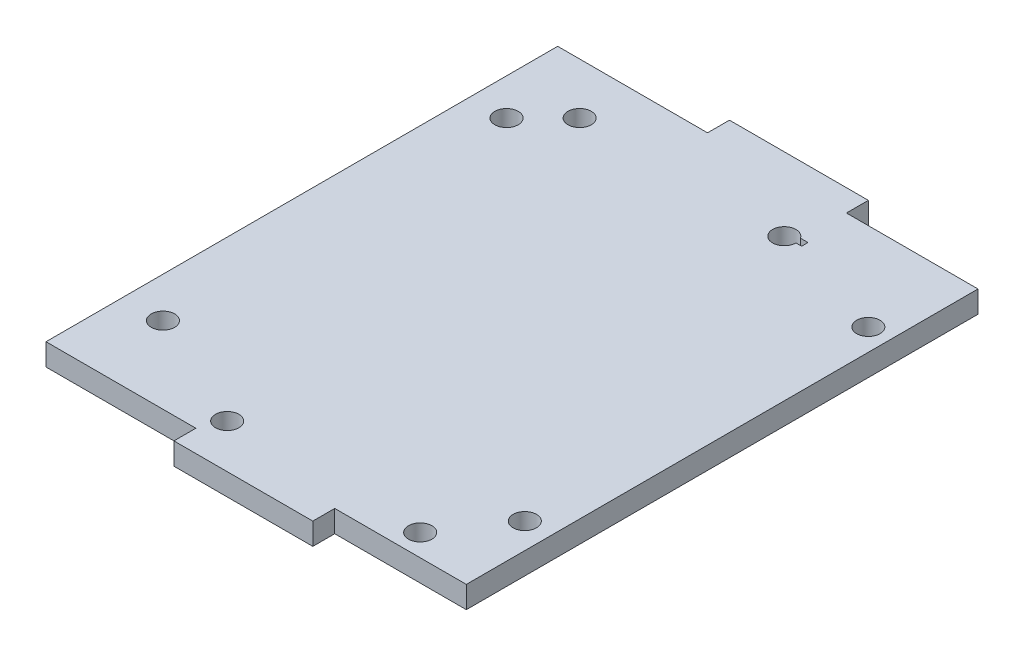
SolidWorks part; units mm, degrees
ref_plane "Front Plane" through (0, 0, 0) normal (0, 0, 1) x (1, 0, 0)
ref_plane "Top Plane" through (0, 0, 0) normal (0, 1, 0) x (1, 0, 0)
ref_plane "Right Plane" through (0, 0, 0) normal (1, 0, 0) x (0, 0, -1)
sketch "Sketch1" plane through (0, 0, 0) normal (0, 1, 0) x (1, 0, 0)
  line L0 (63.7979, -35) -> (63.7979, 35)
  line L1 (8.7979, 35) -> (6.2979, 35)
  line L2 (6.2979, 35) -> (6.2979, -35)
  line L3 (6.2979, -35) -> (8.7979, -35)
  line L5 (45.8979, 28) -> (46.6681, 28)
  line L7 (8.7979, 35) -> (26.7979, 35)
  line L8 (26.7979, 35) -> (26.7979, 38)
  line L9 (26.7979, 38) -> (45.7979, 38)
  line L10 (45.7979, 38) -> (45.7979, 35)
  line L11 (45.7979, 35) -> (63.7979, 35)
  line L12 (45.6375, 28.8749) -> (46.6681, 28.8749)
  line L13 (0, 0) -> (58, 0) construction
  line L14 (46.6681, 28) -> (46.6681, 28.8749)
  line L18 (61, -35) -> (63.7979, -35)
  line L19 (61, 35) -> (63.7979, 35)
  line L25 (36.2979, -34.5) -> (36.2979, 34.5) construction
  line L31 (9.2979, 34.5) -> (63.2979, -34.5) construction
  line L32 (9.2979, -34.5) -> (63.2979, 34.5) construction
  line L37 (61, -35) -> (63.7979, -35)
  line L38 (45.7979, -35) -> (63.7979, -35)
  line L39 (45.7979, -38) -> (45.7979, -35)
  line L40 (26.7979, -38) -> (45.7979, -38)
  line L41 (26.7979, -35) -> (26.7979, -38)
  line L42 (8.7979, -35) -> (26.7979, -35)
  circle A0 centre (11.7979, -24.5) radius 1.6
  circle A1 centre (60.2979, -23.5) radius 1.6
  circle A2 centre (16.2979, 28) radius 1.6
  arc A3 (45.6375, 28.8749) -> (45.8979, 28) centre (44.2979, 28) ccw
  point P29 (36.2979, 0)
  dimension "D14" = 3.2
  dimension "D17" = 3.2
  dimension "D18" = 3.2
  dimension "D19" = 3.2
  dimension "D8" = 28
  dimension "D3" = 48.5
  dimension "D4" = 19
  dimension "D5" = 18
  dimension "D6" = 26.7979
  dimension "D7" = 18
  dimension "D9" = 52.5
  dimension "D10" = 51.5
  dimension "D11" = 3
  dimension "D12" = 69
  dimension "D13" = 7
  dimension "D15" = 2.5
  dimension "D16" = 4.5
  dimension "D23" = 19
extrude "Boss-Extrude1" add sketch "Sketch1" along normal blind 3
sketch "Sketch3" plane through (0, 0, 0) normal (0, -1, 0) x (1, 0, 0)
  line L0 (6.2979, -35) -> (6.2979, 35) construction
  line L1 (6.2979, -35) -> (26.7979, -35) construction
  line L2 (45.7979, -35) -> (63.7979, -35) construction
  circle A0 centre (11.2979, -23) radius 1.6
  circle A1 centre (60.7979, -23) radius 1.6
  circle A2 centre (54.4879, 32) radius 1.6
  circle A3 centre (28.0879, 32) radius 1.6
  dimension "D1" = 3.2
  dimension "D2" = 3.2
  dimension "D3" = 3.2
  dimension "D4" = 3.2
  dimension "D5" = 5
  dimension "D6" = 12
  dimension "D7" = 12
  dimension "D8" = 49.5
  dimension "D9" = 6.31
  dimension "D10" = 55
  dimension "D11" = 26.4
extrude "Cut-Extrude1" cut sketch "Sketch3" against normal blind 10
